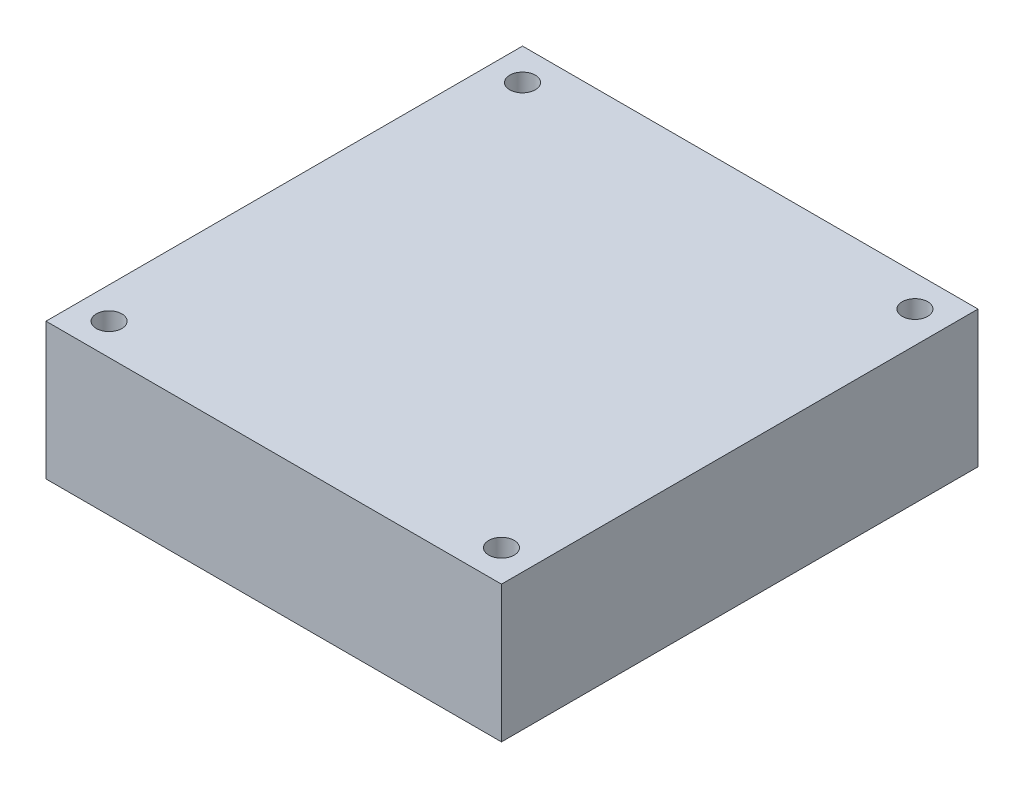
SolidWorks part; units mm, degrees
ref_plane "Front Plane" through (0, 0, 0) normal (0, 0, 1) x (1, 0, 0)
ref_plane "Top Plane" through (0, 0, 0) normal (0, 1, 0) x (1, 0, 0)
ref_plane "Right Plane" through (0, 0, 0) normal (1, 0, 0) x (0, 0, -1)
sketch "Sketch1" plane through (0, 0, 0) normal (0, 1, 0) x (1, 0, 0)
  line L1 (-32.5, 34) -> (32.5, 34)
  line L2 (-32.5, 34) -> (-32.5, -34)
  line L3 (-32.5, -34) -> (32.5, -34)
  line L4 (32.5, 34) -> (32.5, -34)
  line L5 (-32.5, 34) -> (32.5, -34) construction
  line L6 (-32.5, -34) -> (32.5, 34) construction
  point P0 (0, 0)
  dimension "D1" = 65
  dimension "D2" = 68
extrude "Boss-Extrude1" add sketch "Sketch1" along normal blind 19.5
sketch "Sketch2" plane through (0, 19.5, 0) normal (0, 1, 0) x (1, 0, 0)
  line L0 (32.5, -34) -> (32.5, 34) construction
  line L1 (-32.5, -34) -> (32.5, -34) construction
  line L2 (0, 0) -> (0, 26.4913) construction
  line L3 (0, 0) -> (57.4892, 0) construction
  circle A0 centre (28, -29.5) radius 1.8197
  circle A1 centre (-28, -29.5) radius 1.8197
  circle A2 centre (28, 29.5) radius 1.8197
  circle A3 centre (-28, 29.5) radius 1.8197
  dimension "D1" = 4.5
  dimension "D2" = 4.5
extrude "Cut-Extrude1" cut sketch "Sketch2" against normal through all
